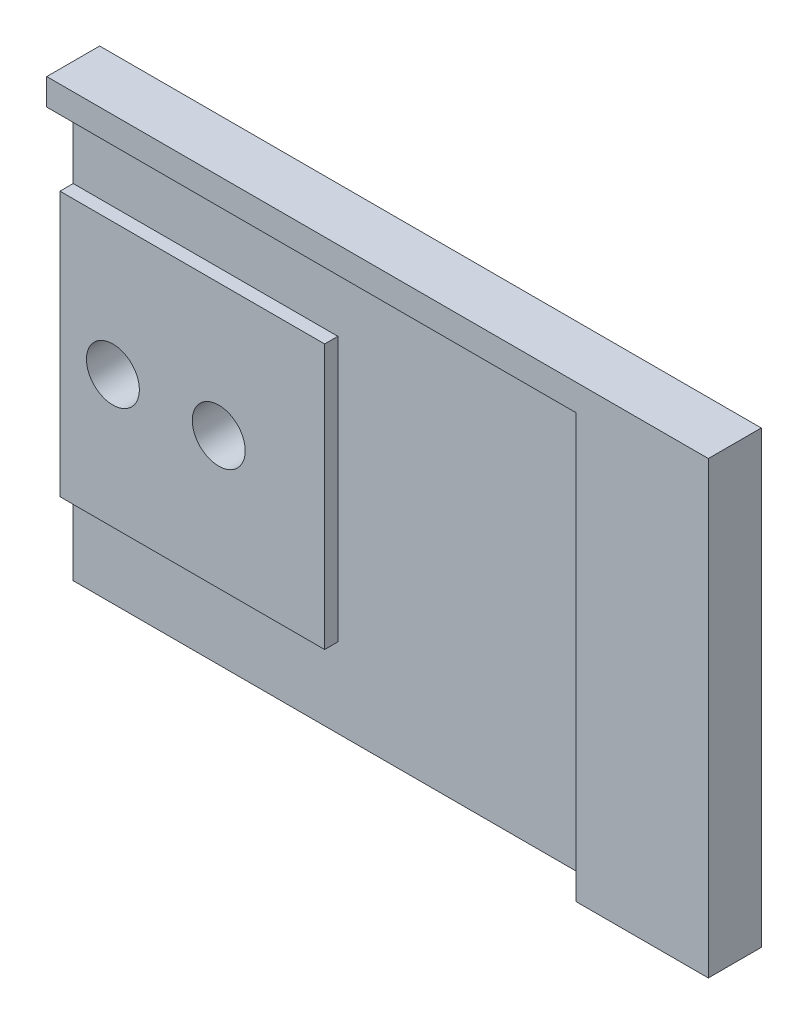
SolidWorks part; units mm, degrees
ref_plane "Ebene vorne" through (0, 0, 0) normal (0, 0, 1) x (1, 0, 0)
ref_plane "Ebene oben" through (0, 0, 0) normal (0, 1, 0) x (1, 0, 0)
ref_plane "Ebene rechts" through (0, 0, 0) normal (1, 0, 0) x (0, 0, -1)
sketch "Skizze1" plane through (0, 0, 0) normal (0, 0, 1) x (1, 0, 0)
  line L1 (-46.2861, 20.7994) -> (78.7139, 20.7994)
  line L2 (-46.2861, 20.7994) -> (-46.2861, -64.2006)
  line L3 (-46.2861, -64.2006) -> (78.7139, -64.2006)
  line L4 (78.7139, 20.7994) -> (78.7139, -64.2006)
  dimension "D1" = 125
  dimension "D2" = 85
extrude "Aufsatz-Linear austragen1" add sketch "Skizze1" along normal blind 10
sketch "Skizze2" plane through (0, 0, 10) normal (0, 0, 1) x (1, 0, 0)
  line L0 (-46.2861, 20.7994) -> (-46.2861, -64.2006) construction
  line L1 (-46.2861, 15.7994) -> (53.7139, 15.7994)
  line L2 (-46.2861, 15.7994) -> (-46.2861, -64.2006)
  line L3 (-46.2861, -64.2006) -> (53.7139, -64.2006)
  line L4 (53.7139, 15.7994) -> (53.7139, -64.2006)
  line L5 (-46.2861, -64.2006) -> (78.7139, -64.2006) construction
  dimension "D1" = 100
  dimension "D2" = 80
extrude "Schnitt-Linear austragen1" cut sketch "Skizze2" against normal blind 5
sketch "Skizze3" plane through (0, 0, 5) normal (0, 0, 1) x (1, 0, 0)
  line L0 (-46.2861, 15.7994) -> (-46.2861, -64.2006) construction
  line L1 (-46.2861, 0.7994) -> (3.7139, 0.7994)
  line L2 (-46.2861, 0.7994) -> (-46.2861, -49.2006)
  line L3 (-46.2861, -49.2006) -> (3.7139, -49.2006)
  line L4 (3.7139, 0.7994) -> (3.7139, -49.2006)
  line L5 (-46.2861, -64.2006) -> (53.7139, -64.2006) construction
  dimension "D1" = 50
  dimension "D2" = 50
  dimension "D3" = 15
extrude "Aufsatz-Linear austragen2" add sketch "Skizze3" along normal blind 2.5
sketch "Skizze4" plane through (0, 0, 7.5) normal (0, 0, 1) x (1, 0, 0)
  line L0 (-46.2861, 0.7994) -> (-46.2861, -49.2006) construction
  circle A0 centre (-36.2861, -24.2006) radius 5
  circle A1 centre (-16.2861, -24.2006) radius 5
  dimension "D1" = 10
  dimension "D2" = 20
extrude "Schnitt-Linear austragen2" cut sketch "Skizze4" against normal blind 22.5
